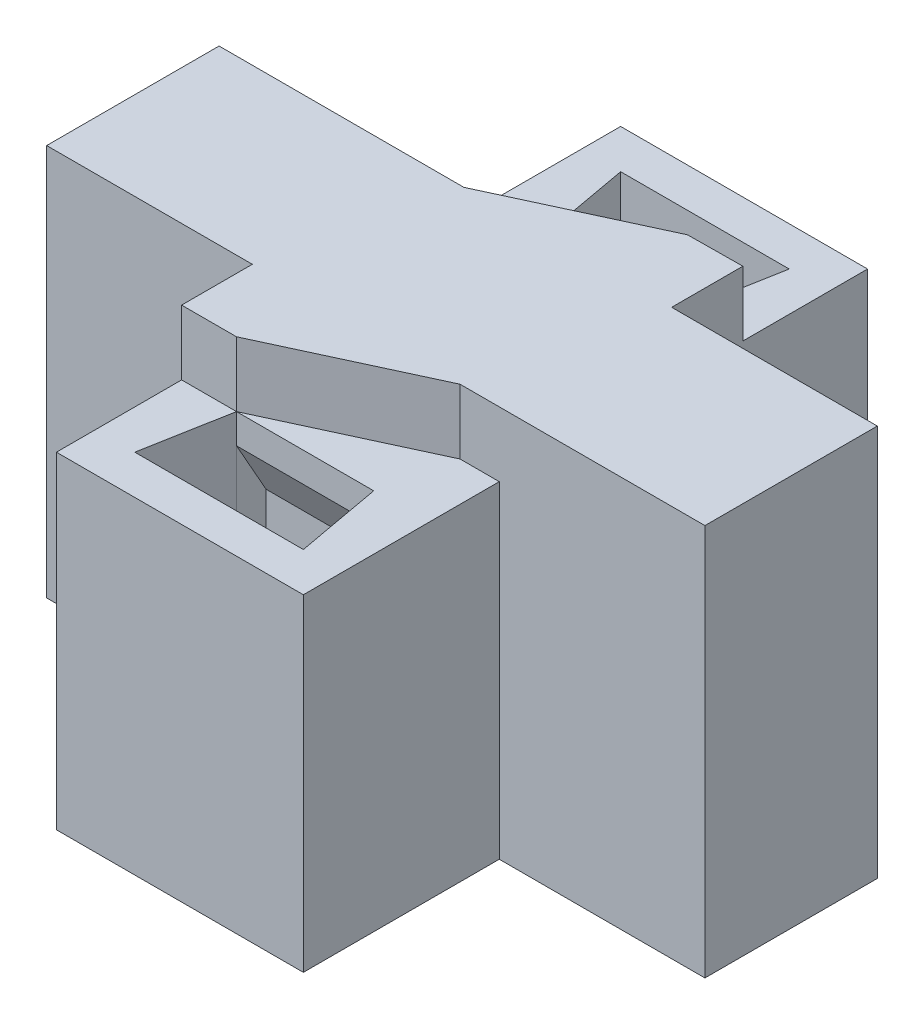
SolidWorks part; units mm, degrees
ref_plane "Front Plane" through (0, 0, 0) normal (0, 0, 1) x (1, 0, 0)
ref_plane "Top Plane" through (0, 0, 0) normal (0, 1, 0) x (1, 0, 0)
ref_plane "Right Plane" through (0, 0, 0) normal (1, 0, 0) x (0, 0, -1)
sketch "Sketch1" plane through (0, 0, 0) normal (0, 1, 0) x (1, 0, 0)
  line L1 (0, 0) -> (106.68, 0)
  line L2 (0, 0) -> (0, -27.94)
  line L3 (0, -27.94) -> (106.68, -27.94)
  line L4 (106.68, 0) -> (106.68, -27.94)
  dimension "D1" = 106.68
  dimension "D2" = 27.94
extrude "Boss-Extrude1" add sketch "Sketch1" along normal blind 63.5
sketch "Sketch2" plane through (0, 0, 0) normal (-1, 0, 0) x (0, 0, 1)
  line L0 (27.94, 63.5) -> (27.94, 0) construction
  line L2 (6.35, 50.8) -> (6.35, 6.35)
  line L3 (6.35, 6.35) -> (21.59, 6.35)
  line L4 (21.59, 50.8) -> (21.59, 6.35)
  line L5 (0, 0) -> (27.94, 0) construction
  line L6 (0, 63.5) -> (0, 0) construction
  spline S0 degree 2 poles (6.35, 50.8) (13.97, 66.04) (21.59, 50.8) knots 0 0 0 1 1 1
  point P14 (13.97, 58.42)
  dimension "D1" = 6.35
  dimension "D2" = 6.35
  dimension "D3" = 6.35
  dimension "D4" = 44.45
extrude "Cut-Extrude2" cut sketch "Sketch2" against normal blind 96.52
sketch "Sketch38" plane through (0, 0, 0) normal (0, 0, -1) x (-1, 0, 0)
  line L0 (-106.68, 63.5) -> (0, 63.5) construction
  line L1 (-73.35, 63.5) -> (-33.33, 63.5)
  line L2 (-73.35, 63.5) -> (-73.35, 0)
  line L3 (-73.35, 0) -> (-33.33, 0)
  line L4 (-33.33, 63.5) -> (-33.33, 0)
  line L5 (-106.68, 0) -> (0, 0) construction
  line L6 (0, 63.5) -> (0, 0) construction
  line L7 (-106.68, 63.5) -> (-106.68, 0) construction
  dimension "D1" = 33.33
  dimension "D2" = 33.33
extrude "Boss-Extrude25" add sketch "Sketch38" along normal blind 6.66
sketch "Sketch40" plane through (0, 0, -6.66) normal (0, 0, -1) x (-1, 0, 0)
  line L0 (-73.35, 0) -> (-33.33, 0) construction
  line L1 (-73.35, 63.5) -> (-67, 63.5)
  line L2 (-73.35, 63.5) -> (-73.35, 0)
  line L3 (-73.35, 0) -> (-67, 0)
  line L4 (-67, 63.5) -> (-67, 0)
  dimension "D1" = 6.35
extrude "Boss-Extrude26" add sketch "Sketch40" along normal blind 18.74
sketch "Sketch41" plane through (0, 0, -6.66) normal (0, 0, -1) x (-1, 0, 0)
  line L0 (-67, 0) -> (-33.33, 0) construction
  line L1 (-33.33, 63.5) -> (-39.68, 63.5)
  line L2 (-33.33, 63.5) -> (-33.33, 0)
  line L3 (-33.33, 0) -> (-39.68, 0)
  line L4 (-39.68, 63.5) -> (-39.68, 0)
  dimension "D1" = 6.35
extrude "Boss-Extrude27" add sketch "Sketch41" along normal blind 18.74
sketch "Sketch43" plane through (0, 0, -6.66) normal (0, 0, -1) x (-1, 0, 0)
  line L0 (-67, 0) -> (-67, 63.5) construction
  line L1 (-67, 17.89) -> (-39.68, 17.89)
  line L2 (-67, 17.89) -> (-67, 0)
  line L3 (-67, 0) -> (-39.68, 0)
  line L4 (-39.68, 17.89) -> (-39.68, 0)
  dimension "D1" = 17.89
extrude "Boss-Extrude28" add sketch "Sketch43" along normal blind 18.74
sketch "Sketch44" plane through (0, 63.5, 0) normal (0, 1, 0) x (1, 0, 0)
  line L0 (73.35, 0) -> (33.33, 0)
  line L1 (33.33, 0) -> (33.33, 25.4)
  line L2 (33.33, 25.4) -> (39.68, 25.4)
  line L3 (39.68, 25.4) -> (39.68, 6.66)
  line L4 (39.68, 6.66) -> (67, 6.66)
  line L5 (67, 6.66) -> (67, 25.4)
  line L6 (67, 25.4) -> (73.35, 25.4)
  line L7 (73.35, 25.4) -> (73.35, 0)
extrude "Cut-Extrude13" cut sketch "Sketch44" against normal blind 10.5
sketch "Sketch46" plane through (0, 0, -6.66) normal (0, 0, -1) x (-1, 0, 0)
  line L0 (-39.68, 53) -> (-39.68, 17.89) construction
  line L1 (-67, 53) -> (-39.68, 53)
  line L2 (-67, 53) -> (-67, 48.2)
  line L3 (-67, 48.2) -> (-39.68, 48.2)
  line L4 (-39.68, 53) -> (-39.68, 48.2)
  dimension "D1" = 4.8
extrude "Boss-Extrude29" add sketch "Sketch46" along normal blind 4.8
sketch "Sketch47" plane through (0, 0, -6.66) normal (0, 0, -1) x (-1, 0, 0)
  line L0 (-67, 39.7) -> (-39.68, 39.7)
  line L1 (-67, 17.89) -> (-67, 48.2) construction
  line L2 (-39.68, 48.2) -> (-39.68, 17.89) construction
  line L3 (-67, 48.2) -> (-39.68, 48.2) construction
  dimension "D1" = 8.5
sketch "Sketch48" plane through (39.68, 0, 0) normal (1, 0, 0) x (0, 0, -1)
  line L0 (11.46, 48.2) -> (6.66, 39.7)
  line L1 (6.66, 39.7) -> (6.66, 48.2)
  line L2 (6.66, 48.2) -> (11.46, 48.2)
extrude "Boss-Extrude30" add sketch "Sketch48" along normal blind 33.36
sketch "Sketch50" plane through (0, 53, 0) normal (0, 1, 0) x (1, 0, 0)
  line L0 (39.68, 11.46) -> (67, 11.46) construction
  line L1 (64.46, 11.46) -> (67, 25.4)
  line L2 (67, 25.4) -> (67, 11.46)
  line L3 (67, 11.46) -> (64.46, 11.46)
  point P0 (64.46, 11.46)
  point P1 (42.59, 11.46)
  dimension "D1" = 2.54
  dimension "D2" = 2.91
extrude "Boss-Extrude31" add sketch "Sketch50" against normal blind 35.11
sketch "Sketch51" plane through (0, 53, 0) normal (0, 1, 0) x (1, 0, 0)
  line L0 (42.22, 11.46) -> (39.68, 11.46)
  line L1 (39.68, 11.46) -> (64.46, 11.46) construction
  line L2 (39.68, 11.46) -> (39.68, 25.4)
  line L3 (39.68, 25.4) -> (42.22, 11.46)
  dimension "D1" = 2.54
extrude "Boss-Extrude32" add sketch "Sketch51" against normal blind 35.11
sketch "Sketch52" plane through (0, 0, -25.4) normal (0, 0, -1) x (-1, 0, 0)
  line L1 (-73.35, 53) -> (-33.33, 53)
  line L2 (-73.35, 53) -> (-73.35, 0)
  line L3 (-73.35, 0) -> (-33.33, 0)
  line L4 (-33.33, 53) -> (-33.33, 0)
extrude "Boss-Extrude33" add sketch "Sketch52" along normal blind 6.35
sketch "Sketch55" plane through (0, 17.89, 0) normal (0, 1, 0) x (1, 0, 0)
  line L1 (64.46, 11.46) -> (67, 11.46)
  line L2 (64.46, 11.46) -> (64.46, 6.66)
  line L3 (64.46, 6.66) -> (67, 6.66)
  line L4 (67, 11.46) -> (67, 6.66)
extrude "Boss-Extrude37" add sketch "Sketch55" along normal blind 35.11
sketch "Sketch56" plane through (0, 17.89, 0) normal (0, 1, 0) x (1, 0, 0)
  line L1 (42.22, 11.46) -> (39.68, 11.46)
  line L2 (42.22, 11.46) -> (42.22, 6.66)
  line L3 (42.22, 6.66) -> (39.68, 6.66)
  line L4 (39.68, 11.46) -> (39.68, 6.66)
extrude "Boss-Extrude38" add sketch "Sketch56" along normal blind 35.11
ref_plane "Plane9" through (0, 0, 13.97) normal (0, 0, -1) x (-1, 0, 0)
mirror "Mirror5" about plane through (0, 0, 13.97) normal (0, 0, -1) of "Boss-Extrude37", "Boss-Extrude38", "Boss-Extrude25", "Boss-Extrude26", "Boss-Extrude27", "Boss-Extrude28", "Cut-Extrude13", "Boss-Extrude29", "Boss-Extrude30", "Boss-Extrude31", "Boss-Extrude32", "Boss-Extrude33"
sketch "Sketch53" plane through (0, 53, 0) normal (0, 1, 0) x (1, 0, 0)
  line L0 (64.46, 11.46) -> (39.68, 0)
  line L1 (33.33, 0) -> (73.35, 0) construction
  line L2 (39.68, 0) -> (73.35, 0)
  line L3 (73.35, 11.5395) -> (64.46, 11.46)
  line L4 (73.35, 0) -> (73.35, 31.75) construction
  line L5 (73.35, 11.5395) -> (73.35, 0)
  dimension "D1" = 6.35
extrude "Boss-Extrude35" add sketch "Sketch53" along normal blind 10.5
sketch "Sketch54" plane through (0, 53, 0) normal (0, 1, 0) x (1, 0, 0)
  line L0 (42.22, -39.4) -> (33.33, -39.4)
  line L1 (33.33, -59.69) -> (33.33, -27.94) construction
  line L2 (33.33, -39.4) -> (33.33, -27.94)
  line L3 (33.33, -27.94) -> (67, -27.94)
  line L4 (33.33, -27.94) -> (73.35, -27.94) construction
  line L5 (67, -27.94) -> (42.22, -39.4)
  dimension "D1" = 6.35
extrude "Boss-Extrude36" add sketch "Sketch54" along normal blind 10.5
